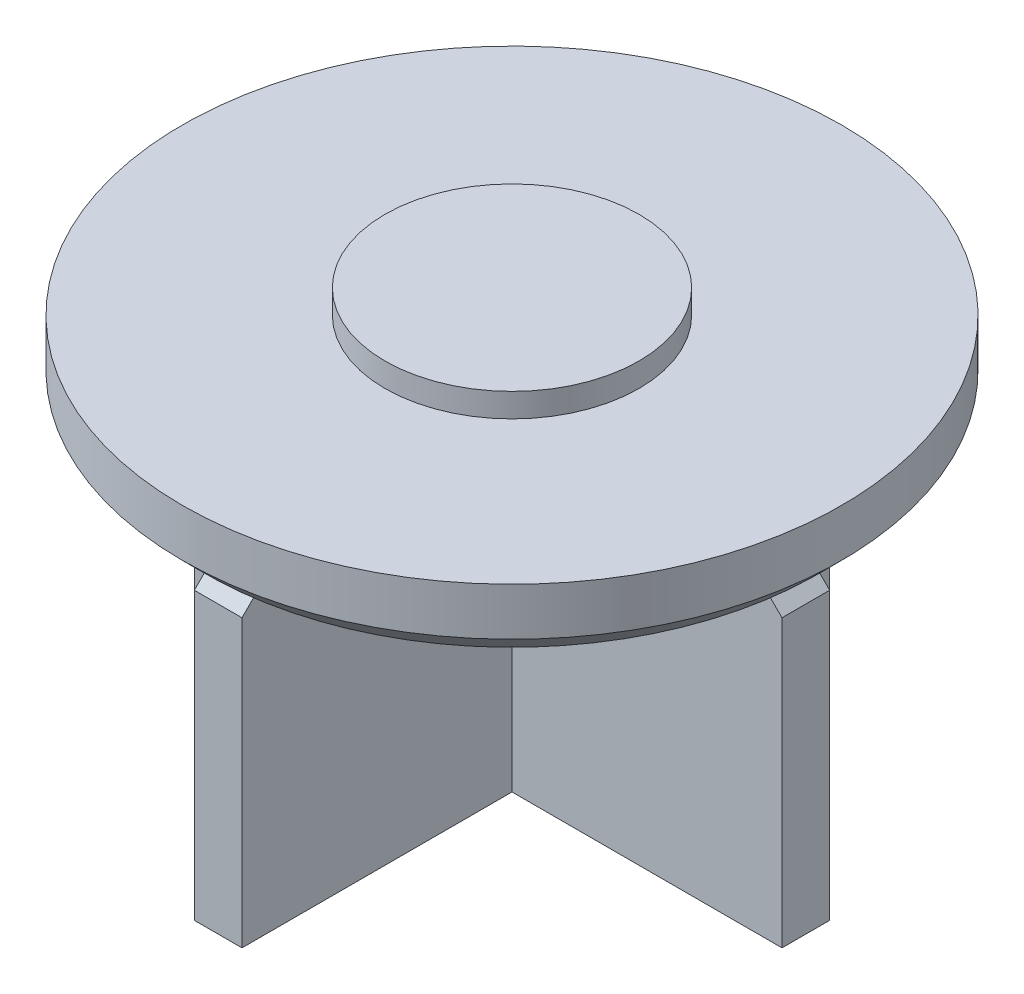
SolidWorks part; units mm, degrees
ref_plane "Front Plane" through (0, 0, 0) normal (0, 0, 1) x (1, 0, 0)
ref_plane "Top Plane" through (0, 0, 0) normal (0, 1, 0) x (1, 0, 0)
ref_plane "Right Plane" through (0, 0, 0) normal (1, 0, 0) x (0, 0, -1)
sketch "Sketch1" plane through (0, 0, 0) normal (0, 0, 1) x (1, 0, 0)
  line L0 (0, 0) -> (-16, 0)
  line L1 (-16, 0) -> (-16, -3)
  line L2 (-16, -3) -> (-41.5, -3)
  line L3 (-41.5, -3) -> (-41.5, -9)
  line L4 (-41.5, -9) -> (-38.5, -12)
  line L5 (-38.5, -12) -> (0, -12)
  line L7 (0, -12) -> (0, 0) construction
  line L8 (0, 0) -> (0, -12)
  dimension "D1" = 32
  dimension "D2" = 83
  dimension "D3" = 6
  dimension "D4" = 45
  dimension "D5" = 3
  dimension "D6" = 3
revolve "Revolve1" add sketch "Sketch1" angle 360 about L7
sketch "Sketch2" plane through (0, 0, 0) normal (0, 0, 1) x (1, 0, 0)
  line L0 (0, -12) -> (0, -52)
  line L1 (0, -52) -> (37, -52)
  line L2 (37, -52) -> (37, -16)
  line L3 (37, -16) -> (33, -12)
  line L4 (-38.5, -12) -> (38.5, -12) construction
  line L5 (33, -12) -> (0, -12)
  line L6 (41.5, -9) -> (-41.5, -9) construction
  point P9 (0, -11.4239)
  dimension "D1" = 43
  dimension "D2" = 37
  dimension "D3" = 4
  dimension "D4" = 45
extrude "Boss-Extrude1" add sketch "Sketch2" along normal mid plane 6
pattern_circular "CirPattern1" count 4 over 360 about axis through (0, 0, 0) along (0, 1, 0) of "Boss-Extrude1"
